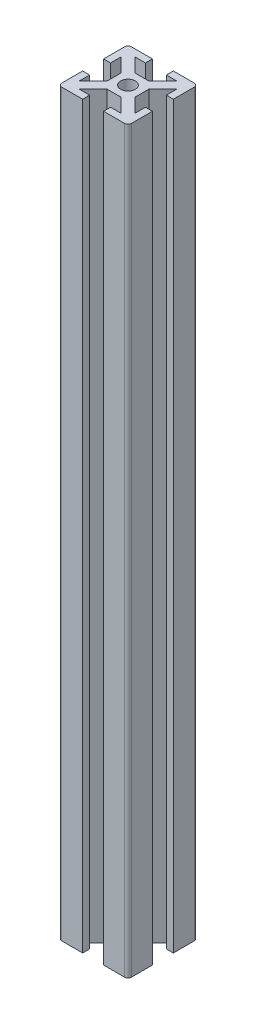
SolidWorks part; units mm, degrees
ref_plane "前视基准面" through (0, 0, 0) normal (0, 0, 1) x (1, 0, 0)
ref_plane "上视基准面" through (0, 0, 0) normal (0, 1, 0) x (1, 0, 0)
ref_plane "右视基准面" through (0, 0, 0) normal (1, 0, 0) x (0, 0, -1)
sketch "草图1" plane through (0, 0, 0) normal (0, 1, 0) x (1, 0, 0)
  line L0 (10, 10) -> (3, 10)
  line L1 (-10, -10) -> (10, -10) construction
  line L2 (-10, -10) -> (-10, 10) construction
  line L3 (-10, 10) -> (10, 10) construction
  line L4 (10, -10) -> (10, 10) construction
  line L5 (-10, -10) -> (10, 10) construction
  line L6 (-10, 10) -> (10, -10) construction
  line L7 (-4, -4) -> (4, -4) construction
  line L8 (-4, -4) -> (-4, 4) construction
  line L9 (-4, 4) -> (4, 4) construction
  line L10 (4, -4) -> (4, 4) construction
  line L11 (-4, -4) -> (4, 4) construction
  line L12 (-4, 4) -> (4, -4) construction
  line L13 (3, 10) -> (3, 8)
  line L14 (3, 8) -> (6, 8)
  line L15 (6, 8) -> (2, 4)
  line L16 (10, 3) -> (8, 3)
  line L17 (8, 6) -> (4, 2)
  line L18 (8, 3) -> (8, 6)
  line L19 (10, 10) -> (10, 3)
  line L20 (8, -6) -> (4, -2)
  line L21 (8, -3) -> (8, -6)
  line L22 (10, -3) -> (8, -3)
  line L23 (10, -10) -> (10, -3)
  line L24 (6, -8) -> (2, -4)
  line L25 (3, -8) -> (6, -8)
  line L26 (3, -10) -> (3, -8)
  line L27 (10, -10) -> (3, -10)
  line L28 (-6, -8) -> (-2, -4)
  line L29 (-3, -8) -> (-6, -8)
  line L30 (-3, -10) -> (-3, -8)
  line L31 (-10, -10) -> (-3, -10)
  line L32 (-8, -6) -> (-4, -2)
  line L33 (-8, -3) -> (-8, -6)
  line L34 (-10, -3) -> (-8, -3)
  line L35 (-10, -10) -> (-10, -3)
  line L36 (-8, 6) -> (-4, 2)
  line L37 (-8, 3) -> (-8, 6)
  line L38 (-10, 3) -> (-8, 3)
  line L39 (-10, 10) -> (-10, 3)
  line L40 (-6, 8) -> (-2, 4)
  line L41 (-3, 8) -> (-6, 8)
  line L42 (-3, 10) -> (-3, 8)
  line L43 (-10, 10) -> (-3, 10)
  line L44 (-4, 2) -> (-4, -2)
  line L45 (-2, -4) -> (2, -4)
  line L46 (4, -2) -> (4, 2)
  line L47 (2, 4) -> (-2, 4)
  circle A0 centre (0, 0) radius 2.1
  point P0 (0, 0)
  point P50 (0, 0)
  dimension "D2" = 4.2
  dimension "D1" = 20
  dimension "D3" = 8
  dimension "D4" = 3
  dimension "D5" = 6
  dimension "D6" = 2
  dimension "D7" = 4
extrude "凸台-拉伸1" add sketch "草图1" along normal blind 650
fillet "圆角1" radius 1 4 edges at (-10, 325, 10) (10, 325, 10) (-10, 325, -10) (10, 325, -10)
sketch "草图2" plane through (0, 650, 0) normal (0, 1, 0) x (1, 0, 0)
  line L36 (10, 3) -> (10, 9)
  line L37 (9, 10) -> (3, 10)
  line L38 (3, 10) -> (3, 8)
  line L39 (3, 8) -> (6, 8)
  line L40 (6, 8) -> (2, 4)
  line L41 (2, 4) -> (-2, 4)
  line L42 (-2, 4) -> (-6, 8)
  line L43 (-6, 8) -> (-3, 8)
  line L44 (-3, 8) -> (-3, 10)
  line L45 (-3, 10) -> (-9, 10)
  line L46 (-10, 9) -> (-10, 3)
  line L47 (-10, 3) -> (-8, 3)
  line L48 (-8, 3) -> (-8, 6)
  line L49 (-8, 6) -> (-4, 2)
  line L50 (-4, 2) -> (-4, -2)
  line L51 (-4, -2) -> (-8, -6)
  line L52 (-8, -6) -> (-8, -3)
  line L53 (-8, -3) -> (-10, -3)
  line L54 (-10, -3) -> (-10, -9)
  line L55 (-9, -10) -> (-3, -10)
  line L56 (-3, -10) -> (-3, -8)
  line L57 (-3, -8) -> (-6, -8)
  line L58 (-6, -8) -> (-2, -4)
  line L59 (-2, -4) -> (2, -4)
  line L60 (2, -4) -> (6, -8)
  line L61 (6, -8) -> (3, -8)
  line L62 (3, -8) -> (3, -10)
  line L63 (3, -10) -> (9, -10)
  line L64 (10, -9) -> (10, -3)
  line L65 (10, -3) -> (8, -3)
  line L66 (8, -3) -> (8, -6)
  line L67 (8, -6) -> (4, -2)
  line L68 (4, -2) -> (4, 2)
  line L69 (4, 2) -> (8, 6)
  line L70 (8, 6) -> (8, 3)
  line L71 (8, 3) -> (10, 3)
  line L72 (10, 3) -> (10, 9)
  line L73 (9, 10) -> (3, 10)
  line L74 (3, 10) -> (3, 8)
  line L75 (3, 8) -> (6, 8)
  line L76 (6, 8) -> (2, 4)
  line L77 (2, 4) -> (-2, 4)
  line L78 (-2, 4) -> (-6, 8)
  line L79 (-6, 8) -> (-3, 8)
  line L80 (-3, 8) -> (-3, 10)
  line L81 (-3, 10) -> (-9, 10)
  line L82 (-10, 9) -> (-10, 3)
  line L83 (-10, 3) -> (-8, 3)
  line L84 (-8, 3) -> (-8, 6)
  line L85 (-8, 6) -> (-4, 2)
  line L86 (-4, 2) -> (-4, -2)
  line L87 (-4, -2) -> (-8, -6)
  line L88 (-8, -6) -> (-8, -3)
  line L89 (-8, -3) -> (-10, -3)
  line L90 (-10, -3) -> (-10, -9)
  line L91 (-9, -10) -> (-3, -10)
  line L92 (-3, -10) -> (-3, -8)
  line L93 (-3, -8) -> (-6, -8)
  line L94 (-6, -8) -> (-2, -4)
  line L95 (-2, -4) -> (2, -4)
  line L96 (2, -4) -> (6, -8)
  line L97 (6, -8) -> (3, -8)
  line L98 (3, -8) -> (3, -10)
  line L99 (3, -10) -> (9, -10)
  line L100 (10, -9) -> (10, -3)
  line L101 (10, -3) -> (8, -3)
  line L102 (8, -3) -> (8, -6)
  line L103 (8, -6) -> (4, -2)
  line L104 (4, -2) -> (4, 2)
  line L105 (4, 2) -> (8, 6)
  line L106 (8, 6) -> (8, 3)
  line L107 (8, 3) -> (10, 3)
  circle A0 centre (0, 0) radius 2.1 construction
  circle A1 centre (0, 0) radius 2.1
  arc A4 (10, 9) -> (9, 10) centre (9, 9) ccw
  arc A5 (-9, 10) -> (-10, 9) centre (-9, 9) ccw
  arc A6 (-10, -9) -> (-9, -10) centre (-9, -9) ccw
  arc A7 (9, -10) -> (10, -9) centre (9, -9) ccw
  arc A8 (10, 9) -> (9, 10) centre (9, 9) ccw
  arc A9 (-9, 10) -> (-10, 9) centre (-9, 9) ccw
  arc A10 (-10, -9) -> (-9, -10) centre (-9, -9) ccw
  arc A11 (9, -10) -> (10, -9) centre (9, -9) ccw
  dimension "D1" = 0
extrude "凸台-拉伸2" [suppressed] add sketch "草图2" along normal blind 550
sketch "草图4" plane through (0, 650, 0) normal (0, 1, 0) x (1, 0, 0)
  line L1 (-10.3551, -10.4669) -> (10.3551, -10.4669)
  line L2 (-10.3551, -10.4669) -> (-10.3551, 10.4669)
  line L3 (-10.3551, 10.4669) -> (10.3551, 10.4669)
  line L4 (10.3551, -10.4669) -> (10.3551, 10.4669)
  line L5 (-10.3551, -10.4669) -> (10.3551, 10.4669) construction
  line L6 (-10.3551, 10.4669) -> (10.3551, -10.4669) construction
  point P0 (0, 0)
extrude "切除-拉伸1" cut sketch "草图4" against normal blind 438
